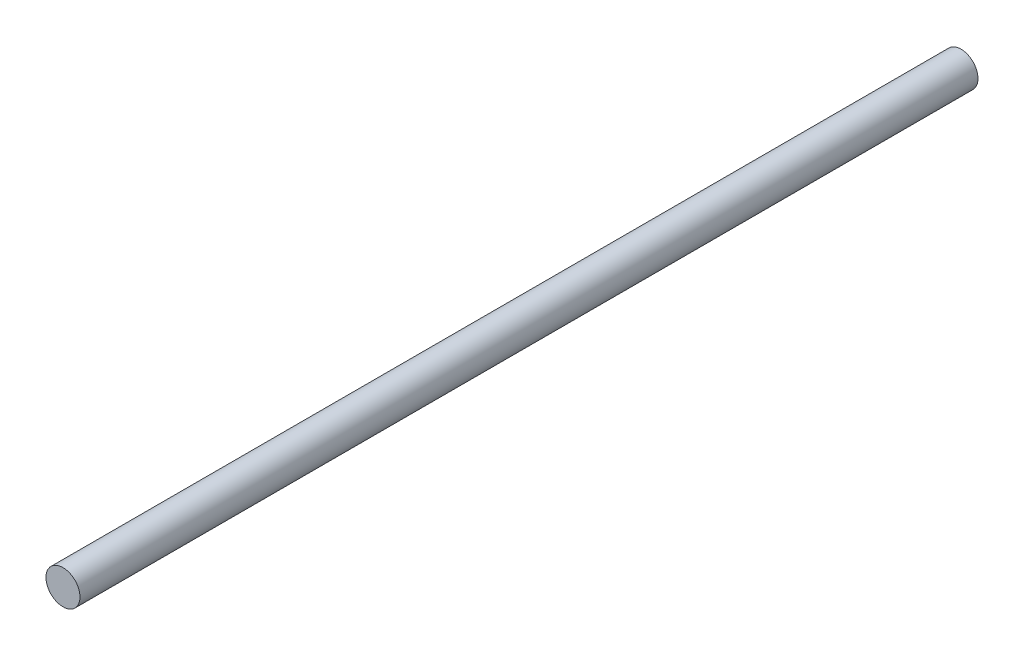
SolidWorks part; units mm, degrees
material "Stainless Steel (ferritic)"
ref_plane "Ön Düzlem" through (0, 0, 0) normal (0, 0, 1) x (1, 0, 0)
ref_plane "Üst Düzlem" through (0, 0, 0) normal (0, 1, 0) x (1, 0, 0)
ref_plane "Sağ Düzlem" through (0, 0, 0) normal (1, 0, 0) x (0, 0, -1)
sketch "Sketch2" plane through (0, 0, 0) normal (0, 0, 1) x (1, 0, 0)
  circle A0 centre (0, 0) radius 5
  dimension "D1" = 10
extrude "Boss-Extrude1" add sketch "Sketch2" along normal blind 264
